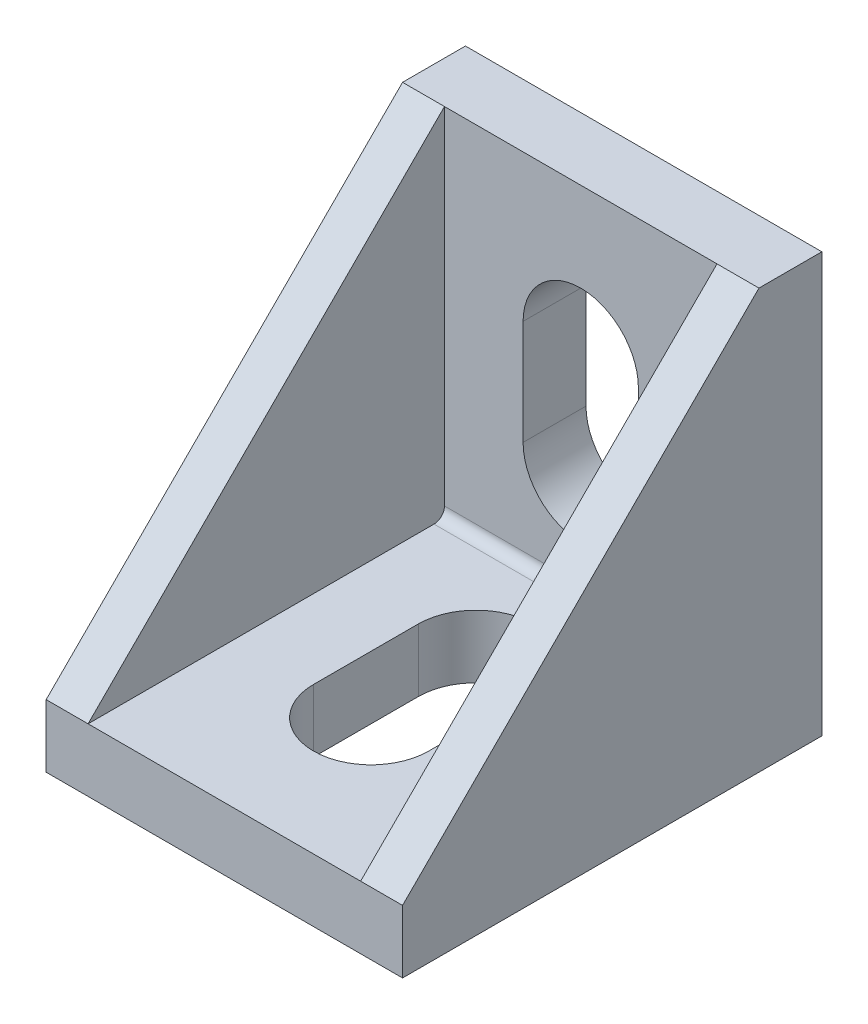
SolidWorks part; units mm, degrees
material "Zinc AG40A (Zn-4Al-0.4Mg; Zamak 3), Cast"
ref_plane "Front Plane" through (0, 0, 0) normal (0, 0, 1) x (1, 0, 0)
ref_plane "Top Plane" through (0, 0, 0) normal (0, 1, 0) x (1, 0, 0)
ref_plane "Right Plane" through (0, 0, 0) normal (1, 0, 0) x (0, 0, -1)
ref_plane "Plane1" through (8.5, 0, 0) normal (1, 0, 0) x (0, 0, -1)
sketch "Sketch16" plane through (8.5, 0, 0) normal (1, 0, 0) x (0, 0, -1)
  line L0 (-3, 3) -> (-3, 20)
  line L1 (-3, 20) -> (-20, 3)
  line L2 (-20, 3) -> (-3, 3)
  dimension "D1" = 17
  dimension "D2" = 17
extrude "Boss-Extrude1" add sketch "Sketch16" against normal blind 17
sketch "Sketch17" plane through (0, 0, 3) normal (0, 0, -1) x (-1, 0, 0)
  line L0 (-8.5, 3) -> (-8.5, 20)
  line L1 (-8.5, 20) -> (8.5, 20)
  line L2 (8.5, 20) -> (8.5, 3)
  line L3 (8.5, 3) -> (-8.5, 3)
  line L4 (-8.5, 3) -> (-8.5, 20) construction
  line L5 (8.5, 3) -> (-8.5, 3) construction
  dimension "D1" = 17
  dimension "D2" = 17
extrude "Boss-Extrude2" add sketch "Sketch17" along normal blind 3
ref_plane "Plane2" through (6.5, 0, 0) normal (1, 0, 0) x (0, 0, -1)
sketch "Sketch22" plane through (6.5, 0, 0) normal (1, 0, 0) x (0, 0, -1)
  line L0 (-3, 20) -> (-20, 3)
  line L1 (-20, 3) -> (-3, 3)
  line L2 (-3, 3) -> (-3, 20)
  dimension "D1" = 17
  dimension "D2" = 17
extrude "Cut-Extrude1" cut sketch "Sketch22" against normal blind 13
sketch "Sketch23" plane through (0, 3, 0) normal (0, -1, 0) x (1, 0, 0)
  line L0 (-8.5, 0) -> (-8.5, 20)
  line L1 (-8.5, 20) -> (8.5, 20)
  line L2 (8.5, 20) -> (8.5, 0)
  line L3 (8.5, 0) -> (-8.5, 0)
  line L4 (-8.5, 20) -> (-8.5, 0) construction
  dimension "D1" = 17
  dimension "D2" = 20
extrude "Boss-Extrude3" add sketch "Sketch23" along normal blind 3
sketch "Sketch24" plane through (0, 0, 0) normal (0, -1, 0) x (1, 0, 0)
  line L0 (6, 0) -> (6, 1)
  line L1 (6, 1) -> (-6, 1)
  line L2 (-6, 1) -> (-6, 0)
  line L3 (-6, 0) -> (6, 0)
  line L4 (8.5, 0) -> (8.5, 20) construction
  line L5 (-8.5, 0) -> (8.5, 0) construction
  dimension "D1" = 2.5
  dimension "D2" = 14.5
  dimension "D3" = 1
extrude "Cut-Extrude2" cut sketch "Sketch24" against normal blind 3
ref_plane "Plane3" through (0, 0, 3) normal (0, 0, 1) x (1, 0, 0)
sketch "Sketch30" plane through (0, 0, 3) normal (0, 0, 1) x (1, 0, 0)
  line L0 (-6, 1) -> (-6, 0)
  line L1 (-6, 0) -> (6, 0)
  line L2 (6, 0) -> (6, 1)
  line L3 (6, 1) -> (-6, 1)
  dimension "D1" = 12
  dimension "D2" = 1
ref_plane "Plane4" through (0, 0, 1) normal (0, 0, -1) x (-1, 0, 0)
extrude "Cut-Extrude3" cut sketch "Sketch30" against normal up to surface (2 mm away) up to plane "Plane4"
sketch "Sketch37" plane through (0, 0, 3) normal (0, 0, 1) x (1, 0, 0)
  line L0 (2.75, 8) -> (2.75, 13)
  line L1 (-2.75, 13) -> (-2.75, 8)
  line L2 (6.5, 3) -> (6.5, 20) construction
  line L3 (-6.5, 20) -> (6.5, 20) construction
  arc A0 (2.75, 13) -> (-2.75, 13) centre (0, 13) ccw
  arc A1 (-2.75, 8) -> (2.75, 8) centre (0, 8) ccw
  dimension "D1" = 2.75
  dimension "D2" = 6.5
  dimension "D3" = 7
  dimension "D4" = 12
extrude "Cut-Extrude4" cut sketch "Sketch37" against normal through all
sketch "Sketch38" plane through (0, 3, 0) normal (0, 1, 0) x (-1, 0, 0)
  line L0 (-2.75, 13) -> (-2.75, 8)
  line L1 (2.75, 8) -> (2.75, 13)
  line L2 (6.5, 20) -> (6.5, 3) construction
  arc A0 (2.75, 13) -> (-2.75, 13) centre (0, 13) ccw
  arc A1 (-2.75, 8) -> (2.75, 8) centre (0, 8) ccw
  dimension "D1" = 2.75
  dimension "D2" = 6.5
  dimension "D3" = 7
  dimension "D4" = 12
extrude "Cut-Extrude5" cut sketch "Sketch38" against normal through all
sketch "Sketch39" plane through (0, 0, 0) normal (0, -1, 0) x (1, 0, 0)
  line L0 (6, 19) -> (-6, 19)
  line L1 (-6, 19) -> (-6, 16)
  line L2 (-6, 16) -> (6, 16)
  line L3 (6, 16) -> (6, 19)
  line L4 (-6, 3) -> (-6, 0) construction
  line L5 (-6, 3) -> (6, 3) construction
  dimension "D1" = 12
  dimension "D2" = 13
  dimension "D3" = 16
extrude "Cut-Extrude6" cut sketch "Sketch39" against normal blind 1
sketch "Sketch40" plane through (0, 1, 0) normal (0, -1, 0) x (1, 0, 0)
  line L0 (-3, 18) -> (3, 18)
  line L1 (3, 18) -> (3, 17)
  line L2 (3, 17) -> (-3, 17)
  line L3 (-3, 17) -> (-3, 18)
  line L4 (6, 16) -> (6, 19) construction
  line L5 (6, 19) -> (-6, 19) construction
  dimension "D1" = 3
  dimension "D2" = 9
  dimension "D3" = 1
  dimension "D4" = 2
extrude "Boss-Extrude4" add sketch "Sketch40" along normal blind 2.5
sketch "Sketch41" plane through (0, 1, 0) normal (0, -1, 0) x (1, 0, 0)
  line L0 (-3, 1) -> (-3, 2)
  line L1 (-3, 2) -> (3, 2)
  line L2 (3, 2) -> (3, 1)
  line L3 (3, 1) -> (-3, 1)
  line L4 (6, 1) -> (6, 3) construction
  line L5 (6, 3) -> (-6, 3) construction
  dimension "D1" = 3
  dimension "D2" = 9
  dimension "D3" = 1
  dimension "D4" = 2
extrude "Boss-Extrude5" add sketch "Sketch41" along normal blind 2.5
ref_plane "Plane5" through (0, 0, -1.5) normal (0, 0, -1) x (-1, 0, 0)
sketch "Sketch49" plane through (0, 0, -1.5) normal (0, 0, -1) x (-1, 0, 0)
  line L0 (3, 1) -> (3, 2)
  line L1 (3, 2) -> (-3, 2)
  line L2 (-3, 2) -> (-3, 1)
  line L3 (-3, 1) -> (3, 1)
  dimension "D1" = 6
  dimension "D2" = 1
extrude "Boss-Extrude6" add sketch "Sketch49" against normal up to next
sketch "Sketch50" plane through (0, 0, 0) normal (0, 0, -1) x (-1, 0, 0)
  line L0 (-6, 16) -> (6, 16)
  line L1 (6, 16) -> (6, 19)
  line L2 (6, 19) -> (-6, 19)
  line L3 (-6, 19) -> (-6, 16)
  line L4 (6, 3) -> (6, 0) construction
  line L5 (6, 3) -> (-6, 3) construction
  dimension "D1" = 12
  dimension "D2" = 13
  dimension "D3" = 16
extrude "Cut-Extrude7" cut sketch "Sketch50" against normal blind 1
sketch "Sketch51" plane through (0, 0, 1) normal (0, 0, -1) x (-1, 0, 0)
  line L0 (3, 17) -> (-3, 17)
  line L1 (-3, 17) -> (-3, 18)
  line L2 (-3, 18) -> (3, 18)
  line L3 (3, 18) -> (3, 17)
  line L4 (-6, 19) -> (-6, 16) construction
  line L5 (-6, 16) -> (6, 16) construction
  dimension "D1" = 3
  dimension "D2" = 9
  dimension "D3" = 1
  dimension "D4" = 2
extrude "Boss-Extrude7" add sketch "Sketch51" along normal blind 2.5
fillet "Fillet1" radius 0.5 1 edges at (0, 3, 3)
